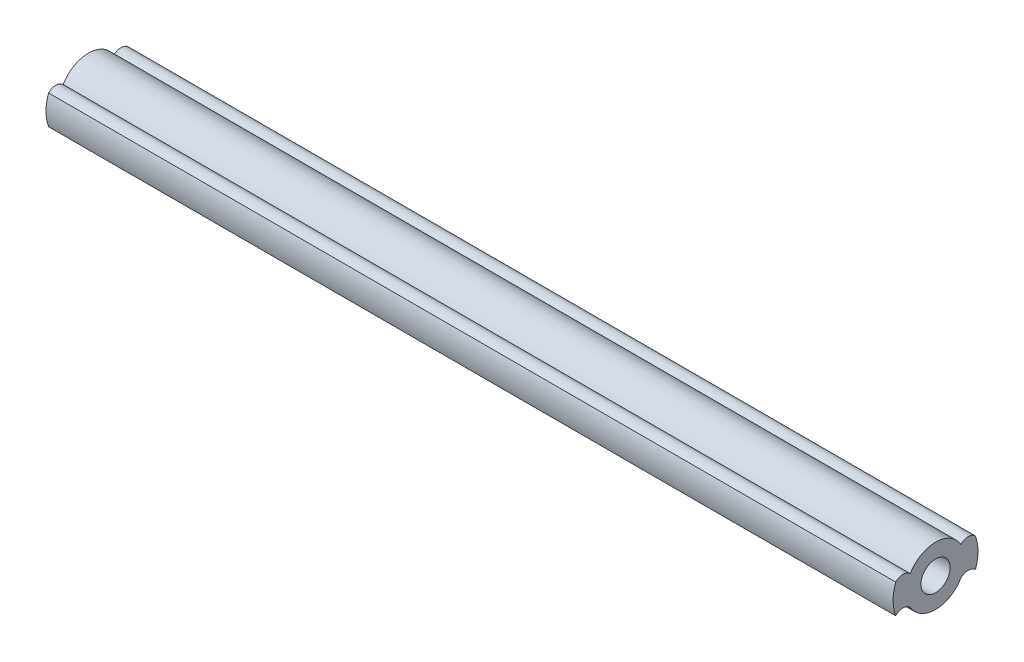
SolidWorks part; units mm, degrees
ref_plane "Front Plane" through (0, 0, 0) normal (0, 0, 1) x (1, 0, 0)
ref_plane "Top Plane" through (0, 0, 0) normal (0, 1, 0) x (1, 0, 0)
ref_plane "Right Plane" through (0, 0, 0) normal (1, 0, 0) x (0, 0, -1)
sketch "Sketch1" plane through (0, 0, 0) normal (1, 0, 0) x (0, 0, -1)
  circle A0 centre (0, 0) radius 10
  circle A1 centre (0, 0) radius 5
  arc A5 (8.6562, 5.007) -> (8.6538, -5.0112) centre (0, 0) cw
  arc A6 (8.6538, -5.0112) -> (13.6624, -5.0091) centre (11.1592, -7.5144) cw
  arc A7 (8.6562, 5.007) -> (13.6624, 5) centre (11.1559, 2.5004) cw
  arc A8 (13.6624, 5) -> (13.6624, -5.0091) centre (-0.2704, -0.0045) cw
  arc A9 (5, 8.6603) -> (5, -8.6603) centre (0, 0) cw
  arc A10 (-8.6562, 5.007) -> (-13.6624, 5) centre (-11.1559, 2.5004) ccw
  arc A11 (-8.6562, 5.007) -> (-8.6538, -5.0112) centre (0, 0) ccw
  arc A12 (-8.6538, -5.0112) -> (-13.6624, -5.0091) centre (-11.1592, -7.5144) ccw
  arc A13 (-13.6624, 5) -> (-13.6624, -5.0091) centre (0.2704, -0.0045) ccw
  circle A14 centre (4.9773, 0.2164) radius 0.018
  dimension "D1" = 20
  dimension "D2" = 10
extrude "Boss-Extrude1" add sketch "Sketch1" along normal blind 290 contours A0 A1 | A8 A7 A0 A6 | A10 A13 A12 A0
